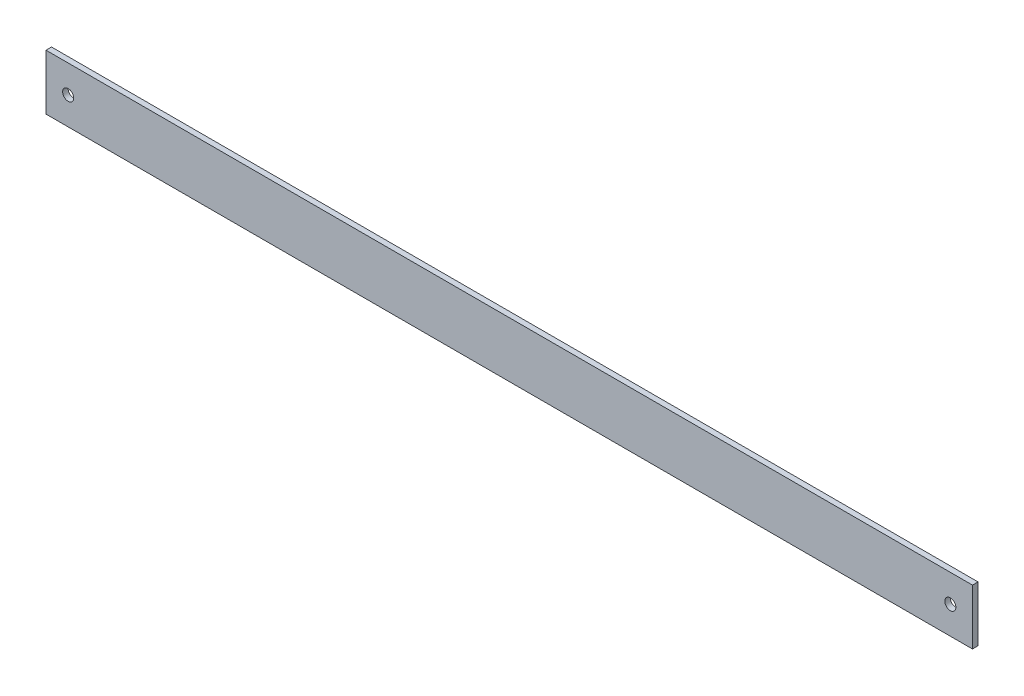
SolidWorks part; units mm, degrees
ref_plane "Plan de face" through (0, 0, 0) normal (0, 0, 1) x (1, 0, 0)
ref_plane "Plan de dessus" through (0, 0, 0) normal (0, 1, 0) x (1, 0, 0)
ref_plane "Plan de droite" through (0, 0, 0) normal (1, 0, 0) x (0, 0, -1)
sketch "Esquisse1" plane through (0, 0, 0) normal (0, 0, 1) x (1, 0, 0)
  line L1 (-286.9096, 1668.032) -> (-35.9096, 1668.032)
  line L2 (-286.9096, 1668.032) -> (-286.9096, 1683.032)
  line L3 (-286.9096, 1683.032) -> (-35.9096, 1683.032)
  line L4 (-35.9096, 1668.032) -> (-35.9096, 1683.032)
  dimension "D1" = 251
  dimension "D2" = 15
extrude "Extrusion1" add sketch "Esquisse1" along normal blind 1.5
sketch "Esquisse2" plane through (0, 0, 0) normal (0, 0, -1) x (-1, 0, 0)
  line L0 (286.9096, 1683.032) -> (286.9096, 1668.032) construction
  line L1 (35.9096, 1668.032) -> (35.9096, 1683.032) construction
  line L2 (35.9096, 1683.032) -> (286.9096, 1683.032) construction
  line L3 (286.9096, 1668.032) -> (35.9096, 1668.032) construction
  circle A0 centre (280.9096, 1675.532) radius 1.5
  circle A1 centre (41.9096, 1675.532) radius 1.5
  point P6 (35.9096, 1675.532)
  dimension "D1" = 6
  dimension "D2" = 6
  dimension "D3" = 7.5
  dimension "D4" = 7.5
extrude "Extrusion2" cut sketch "Esquisse2" against normal blind 1.5
